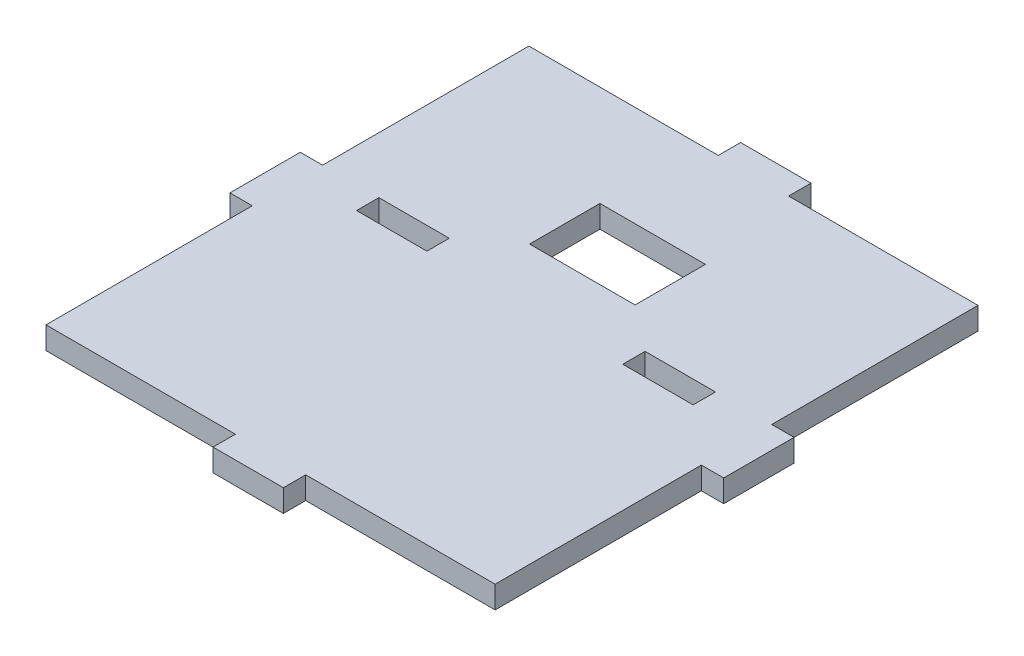
SolidWorks part; units mm, degrees
ref_plane "Front Plane" through (0, 0, 0) normal (0, 0, 1) x (1, 0, 0)
ref_plane "Top Plane" through (0, 0, 0) normal (0, 1, 0) x (1, 0, 0)
ref_plane "Right Plane" through (0, 0, 0) normal (1, 0, 0) x (0, 0, -1)
sketch "Sketch1" plane through (0, 0, 0) normal (0, 1, 0) x (1, 0, 0)
  line L0 (0, -55) -> (0, 55) construction
  line L1 (-127.7, -137.3) -> (127.7, -137.3)
  line L2 (-127.7, -137.3) -> (-127.7, 137.3)
  line L3 (-127.7, 137.3) -> (127.7, 137.3)
  line L4 (127.7, -137.3) -> (127.7, 137.3)
  line L5 (-127.7, -137.3) -> (127.7, 137.3) construction
  line L6 (-127.7, 137.3) -> (127.7, -137.3) construction
  line L7 (127.7, 20) -> (140.4, 20)
  line L8 (127.7, 20) -> (127.7, -20)
  line L9 (127.7, -20) -> (140.4, -20)
  line L10 (140.4, 20) -> (140.4, -20)
  line L11 (-20, 137.3) -> (20, 137.3)
  line L12 (-20, 137.3) -> (-20, 150)
  line L13 (-20, 150) -> (20, 150)
  line L14 (20, 137.3) -> (20, 150)
  line L15 (-127.7, -20) -> (-140.4, -20)
  line L16 (-140.4, 20) -> (-140.4, -20)
  line L17 (-127.7, 20) -> (-140.4, 20)
  line L18 (-127.7, 20) -> (-127.7, -20)
  line L19 (-55, 0) -> (55, 0) construction
  line L20 (-20, -150) -> (20, -150)
  line L21 (20, -137.3) -> (20, -150)
  line L22 (-20, -137.3) -> (20, -137.3)
  line L23 (-20, -137.3) -> (-20, -150)
  point P0 (0, 0)
  dimension "D1" = 255.4
  dimension "D2" = 274.6
  dimension "D3" = 12.7
  dimension "D4" = 40
  dimension "D5" = 12.7
  dimension "D6" = 40
  dimension "D7" = 107.7
  dimension "D8" = 117.3
extrude "Boss-Extrude1" add sketch "Sketch1" along normal blind 12.7 contours L10 L7 L4 L9 | L1 L23 L20 L21 | L16 L15 L18 L17 | L13 L14 L11 L12
sketch "Sketch2" plane through (0, 12.7, 0) normal (0, 1, 0) x (1, 0, 0)
  line L0 (-127.7, 20) -> (-140.4, 20) construction
  line L1 (-95.7, 20) -> (-55.7, 20)
  line L2 (-95.7, 20) -> (-95.7, 7.3)
  line L3 (-95.7, 7.3) -> (-55.7, 7.3)
  line L4 (-55.7, 20) -> (-55.7, 7.3)
  line L5 (55.7, 20) -> (95.7, 20)
  line L6 (55.7, 20) -> (55.7, 7.3)
  line L7 (55.7, 7.3) -> (95.7, 7.3)
  line L8 (95.7, 20) -> (95.7, 7.3)
  line L9 (0, 150) -> (0, 80) construction
  line L10 (-140.4, 20) -> (-140.4, -20) construction
  line L11 (140.4, 20) -> (140.4, -20) construction
  line L12 (-30, 40) -> (30, 40)
  line L13 (-30, 40) -> (-30, 80)
  line L14 (-30, 80) -> (30, 80)
  line L15 (30, 40) -> (30, 80)
  line L16 (-20, 150) -> (20, 150) construction
  dimension "D1" = 12.7
  dimension "D2" = 12.7
  dimension "D3" = 40
  dimension "D4" = 40
  dimension "D5" = 44.7
  dimension "D6" = 44.7
  dimension "D7" = 20
  dimension "D8" = 40
  dimension "D9" = 60
extrude "Cut-Extrude1" cut sketch "Sketch2" against normal blind 12.7
